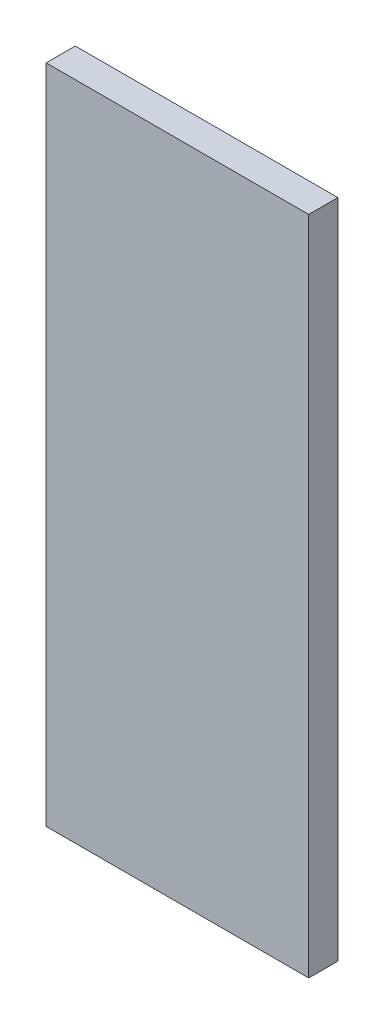
SolidWorks part; units mm, degrees
material "Polyurethane Foam Rigid"
ref_plane "Front Plane" through (0, 0, 0) normal (0, 0, 1) x (1, 0, 0)
ref_plane "Top Plane" through (0, 0, 0) normal (0, 1, 0) x (1, 0, 0)
ref_plane "Right Plane" through (0, 0, 0) normal (1, 0, 0) x (0, 0, -1)
sketch "Sketch1" plane through (0, 0, 0) normal (0, 0, 1) x (1, 0, 0)
  line L1 (-342.9, -863.6) -> (342.9, -863.6)
  line L2 (-342.9, -863.6) -> (-342.9, 863.6)
  line L3 (-342.9, 863.6) -> (342.9, 863.6)
  line L4 (342.9, -863.6) -> (342.9, 863.6)
  line L5 (-342.9, -863.6) -> (342.9, 863.6) construction
  line L6 (-342.9, 863.6) -> (342.9, -863.6) construction
  point P0 (0, 0)
  point P5 (0, 0)
extrude "Boss-Extrude1" add sketch "Sketch1" along normal blind 76.2
